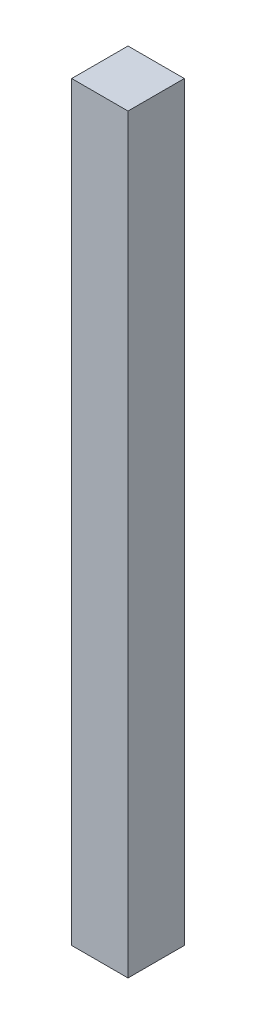
SolidWorks part; units mm, degrees
ref_plane "Front Plane" through (0, 0, 0) normal (0, 0, 1) x (1, 0, 0)
ref_plane "Top Plane" through (0, 0, 0) normal (0, 1, 0) x (1, 0, 0)
ref_plane "Right Plane" through (0, 0, 0) normal (1, 0, 0) x (0, 0, -1)
sketch "Sketch1" plane through (0, 0, 0) normal (0, 1, 0) x (1, 0, 0)
  line L1 (7.5, -7.5) -> (-7.5, -7.5)
  line L2 (7.5, -7.5) -> (7.5, 7.5)
  line L3 (7.5, 7.5) -> (-7.5, 7.5)
  line L4 (-7.5, -7.5) -> (-7.5, 7.5)
  line L5 (7.5, -7.5) -> (-7.5, 7.5) construction
  line L6 (7.5, 7.5) -> (-7.5, -7.5) construction
  point P0 (0, 0)
  dimension "D1" = 15
  dimension "D2" = 15
extrude "Boss-Extrude1" add sketch "Sketch1" along normal mid plane 200
